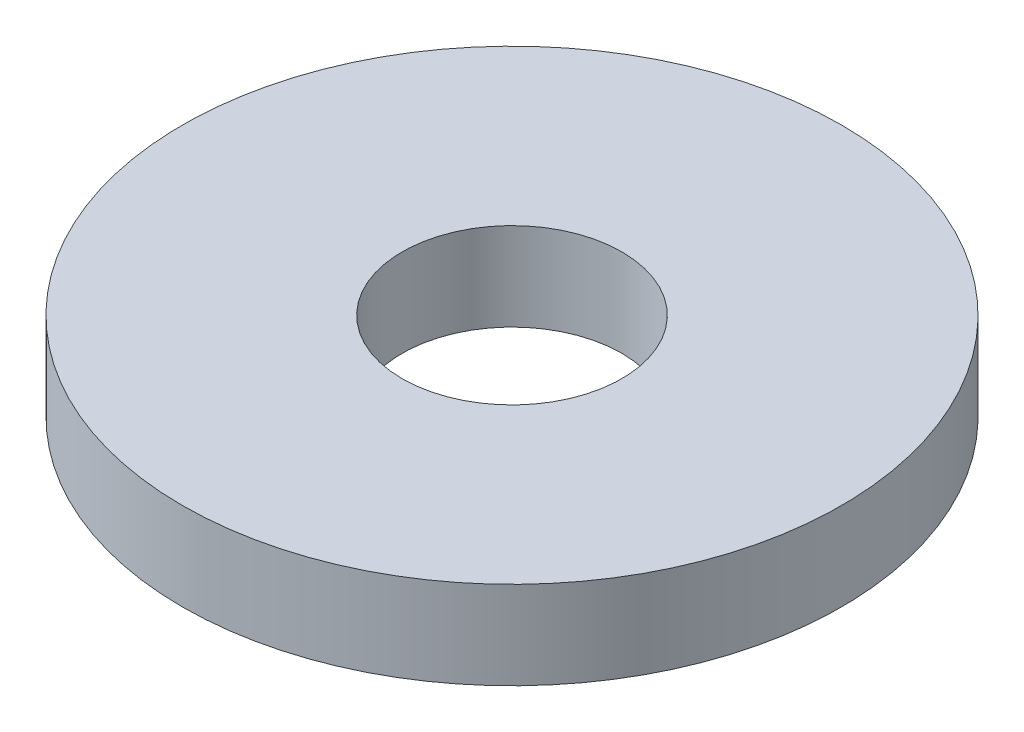
SolidWorks part; units mm, degrees
ref_plane "Front" through (0, 0, 0) normal (0, 0, 1) x (1, 0, 0)
ref_plane "Top" through (0, 0, 0) normal (0, 1, 0) x (1, 0, 0)
ref_plane "Right" through (0, 0, 0) normal (1, 0, 0) x (0, 0, -1)
sketch "Sketch1" plane through (0, 0, 0) normal (0, 1, 0) x (1, 0, 0)
  circle A0 centre (0, 0) radius 15
  circle A1 centre (0, 0) radius 5
  dimension "D1" = 30
  dimension "D2" = 10
extrude "Boss-Extrude1" add sketch "Sketch1" along normal blind 4
